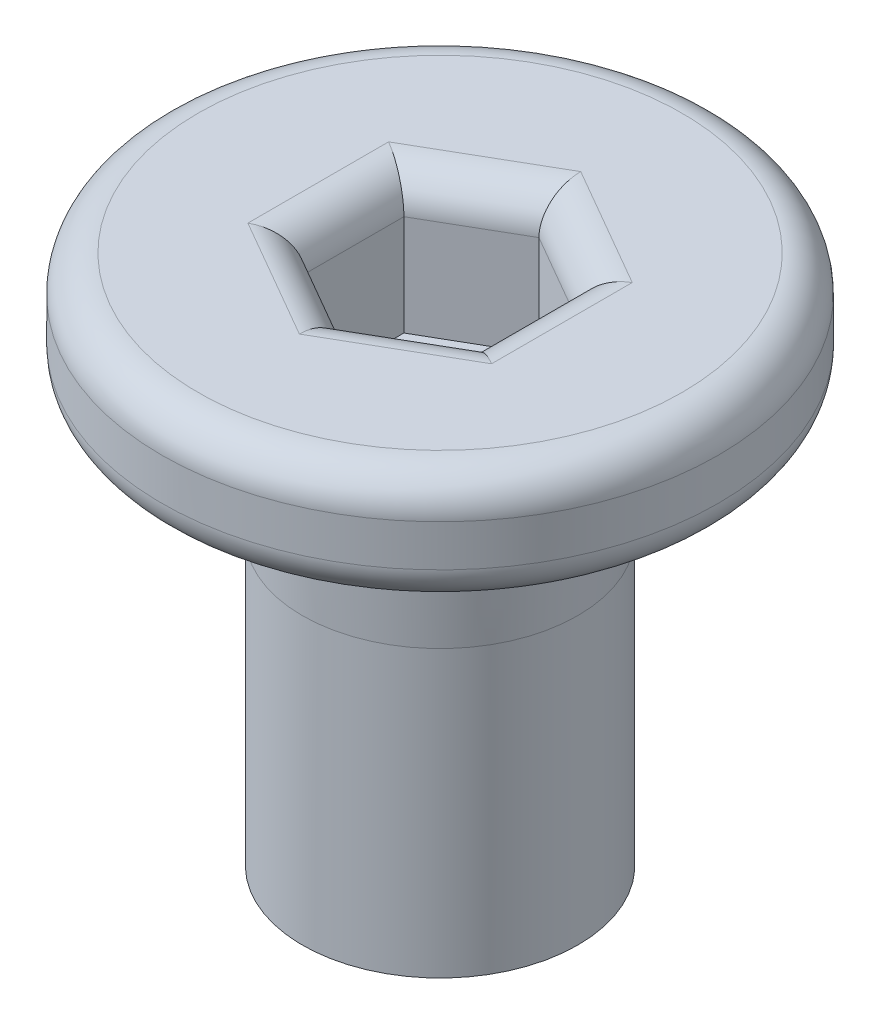
SolidWorks part; units mm, degrees
ref_plane "Front Plane" through (0, 0, 0) normal (0, 0, 1) x (1, 0, 0)
ref_plane "Top Plane" through (0, 0, 0) normal (0, 1, 0) x (1, 0, 0)
ref_plane "Right Plane" through (0, 0, 0) normal (1, 0, 0) x (0, 0, -1)
sketch "Sketch2" plane through (0, 0, 0) normal (0, 0, 1) x (1, 0, 0)
  line L0 (0, -4.65) -> (0, 4.65) construction
  line L1 (0, 4.65) -> (4.875, 4.65)
  line L2 (4.875, 4.65) -> (4.875, 2.65)
  line L3 (4.875, 2.65) -> (2.5, 2.65)
  line L4 (2.5, 2.65) -> (2.413, 0.35)
  line L5 (2.413, 0.35) -> (2.413, -4.65)
  line L6 (2.413, -4.65) -> (0, -4.65)
  line L7 (0, -4.65) -> (0, 4.65)
  point P4 (4.875, 3.65)
  point P5 (0, 0)
  dimension "D1" = 9.3
  dimension "D2" = 2.413
  dimension "D3" = 4.875
  dimension "D4" = 2
  dimension "D5" = 2.5
  dimension "D6" = 2.3
revolve "Revolve1" add sketch "Sketch2" angle 360 about L0
fillet "Fillet1" radius 0.635 3 edges at (2.5, 2.65, 0) (4.875, 4.65, 0) (4.875, 2.65, 0)
sketch "Sketch3" plane through (0, 4.65, 0) normal (0, 1, 0) x (1, 0, 0)
  line L1 (0, 1.7321) -> (-1.5, 0.866)
  line L2 (-1.5, 0.866) -> (-1.5, -0.866)
  line L3 (-1.5, -0.866) -> (0, -1.7321)
  line L4 (0, -1.7321) -> (1.5, -0.866)
  line L5 (1.5, -0.866) -> (1.5, 0.866)
  line L6 (1.5, 0.866) -> (0, 1.7321)
  circle A0 centre (0, 0) radius 1.5 construction
  dimension "D1" = 3
extrude "Cut-Extrude1" cut sketch "Sketch3" against normal blind 2.4
fillet "Fillet2" radius 0.635 6 edges at (-0.75, 4.65, -1.299) (-1.5, 4.65, 0) (-0.75, 4.65, 1.299) (0.75, 4.65, 1.299) (1.5, 4.65, 0) (0.75, 4.65, -1.299)
